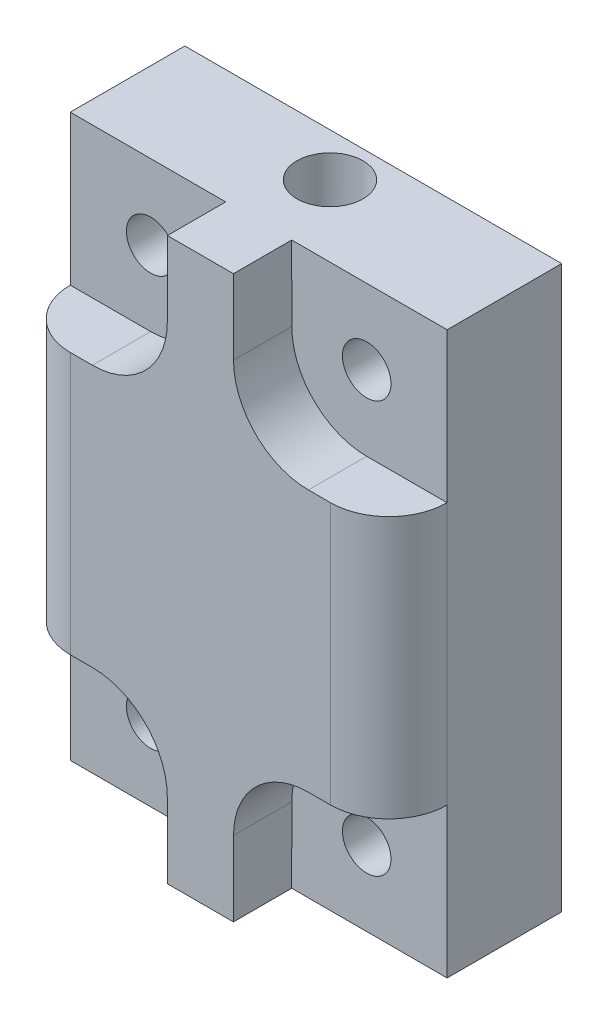
SolidWorks part; units mm, degrees
ref_plane "Front Plane" through (0, 0, 0) normal (0, 0, 1) x (1, 0, 0)
ref_plane "Top Plane" through (0, 0, 0) normal (0, 1, 0) x (1, 0, 0)
ref_plane "Right Plane" through (0, 0, 0) normal (1, 0, 0) x (0, 0, -1)
sketch "Sketch1" plane through (0, 0, 0) normal (0, 1, 0) x (1, 0, 0)
  line L0 (-9.7, 0) -> (9.7, 0)
  line L1 (-9.7, 0) -> (-9.7, -5.9)
  line L2 (9.7, -5.9) -> (9.7, 0)
  line L3 (-6.7, -8.9) -> (6.7, -8.9)
  arc A0 (-9.7, -5.9) -> (-6.7, -8.9) centre (-6.7, -5.9) ccw
  arc A1 (6.7, -8.9) -> (9.7, -5.9) centre (6.7, -5.9) ccw
  circle A2 centre (0, -2.23) radius 1.7
extrude "Boss-Extrude1" add sketch "Sketch1" along normal blind 28.9
sketch "Sketch2" plane through (0, 0, 0) normal (0, 0, -1) x (-1, 0, 0)
  circle A1 centre (5.56, 25.0442) radius 1.25
  circle A2 centre (5.56, 3.8558) radius 1.25
  circle A3 centre (-5.56, 3.8558) radius 1.25
  circle A4 centre (-5.56, 25.0442) radius 1.25
extrude "Cut-Extrude1" cut sketch "Sketch2" against normal up to surface (8.9 mm away) up to face at (0, 14.45, 8.9)
sketch "Sketch3" plane through (0, 0, 8.9) normal (0, 0, 1) x (1, 0, 0)
  line L0 (5.56, 7.7115) -> (9.7, 7.7115)
  line L4 (9.7, 0) -> (9.7, 7.7115)
  line L5 (5.56, 21.1885) -> (9.7, 21.1885)
  line L6 (9.7, 21.1885) -> (9.7, 28.9)
  line L8 (-1.7042, 3.8558) -> (-1.7, 0)
  line L10 (-9.7, 28.9) -> (-9.7, 21.1885)
  line L12 (-9.7, 21.1885) -> (-5.56, 21.1885)
  line L13 (1.7042, 3.8558) -> (1.7, 0)
  line L14 (-5.56, 7.7115) -> (-9.7, 7.7115)
  line L15 (-9.7, 7.7115) -> (-9.7, 0)
  line L18 (-1.7, 0) -> (-9.7, 0)
  line L19 (1.7042, 25.0442) -> (1.7, 28.9)
  line L20 (1.7, 0) -> (9.7, 0)
  line L21 (-1.7042, 25.0442) -> (-1.7, 28.9)
  line L22 (9.7, 28.9) -> (1.7, 28.9)
  line L23 (-9.7, 28.9) -> (-1.7, 28.9)
  arc A0 (-1.7042, 3.8558) -> (-5.56, 7.7115) centre (-5.56, 3.8558) ccw
  arc A1 (5.56, 7.7115) -> (1.7042, 3.8558) centre (5.56, 3.8558) ccw
  arc A2 (-5.56, 21.1885) -> (-1.7042, 25.0442) centre (-5.56, 25.0442) ccw
  arc A3 (1.7042, 25.0442) -> (5.56, 21.1885) centre (5.56, 25.0442) ccw
extrude "Cut-Extrude2" cut sketch "Sketch3" against normal up to vertex (3 mm away)
sketch "Sketch4" plane through (0, 0, 0) normal (0, 0, -1) x (-1, 0, 0)
  circle A0 centre (0, 14.45) radius 2.5
  circle A1 centre (0, 14.45) radius 3.5
extrude "Boss-Extrude2" add sketch "Sketch4" along normal blind 0.4
sketch "Sketch5" plane through (0, 0, -0.4) normal (0, 0, -1) x (-1, 0, 0)
  circle A0 centre (0, 14.45) radius 2.5
extrude "Cut-Extrude3" cut sketch "Sketch5" against normal blind 3.5
